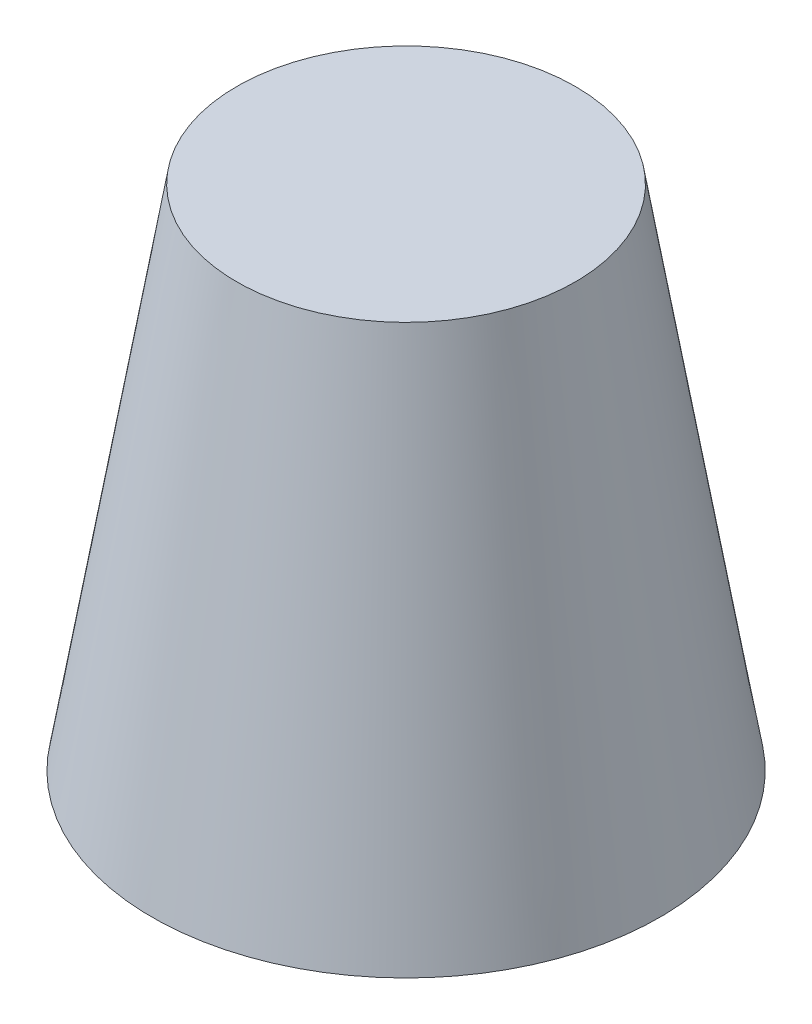
SolidWorks part; units mm, degrees
ref_plane "前视基准面" through (0, 0, 0) normal (0, 0, 1) x (1, 0, 0)
ref_plane "上视基准面" through (0, 0, 0) normal (0, 1, 0) x (1, 0, 0)
ref_plane "右视基准面" through (0, 0, 0) normal (1, 0, 0) x (0, 0, -1)
other "Configuration Table"
sketch "草图1" plane through (0, 0, 0) normal (0, 0, 1) x (1, 0, 0)
  line L0 (0, 0) -> (0, 60)
  line L1 (0, 60) -> (20, 60)
  line L2 (20, 60) -> (30, 0)
  line L3 (30, 0) -> (0, 0)
  line L12 (26.4586, 3) -> (3, 3)
  line L13 (3, 3) -> (3, 57)
  line L14 (3, 57) -> (17.4586, 57)
  line L15 (17.4586, 57) -> (26.4586, 3)
  line L16 (3, 57) -> (0, 57)
  line L17 (3, 3) -> (3, 0)
  line L18 (0, 0) -> (25, 0)
  line L19 (25, 0) -> (12, 50)
  line L20 (12, 50) -> (0, 50)
  dimension "D1" = 20
  dimension "D2" = 30
  dimension "D3" = 60
  dimension "D5" = 12
  dimension "D6" = 25
  dimension "D7" = 50
  dimension "D4" = 3
revolve "旋转1" add sketch "草图1" angle 360 about L0
